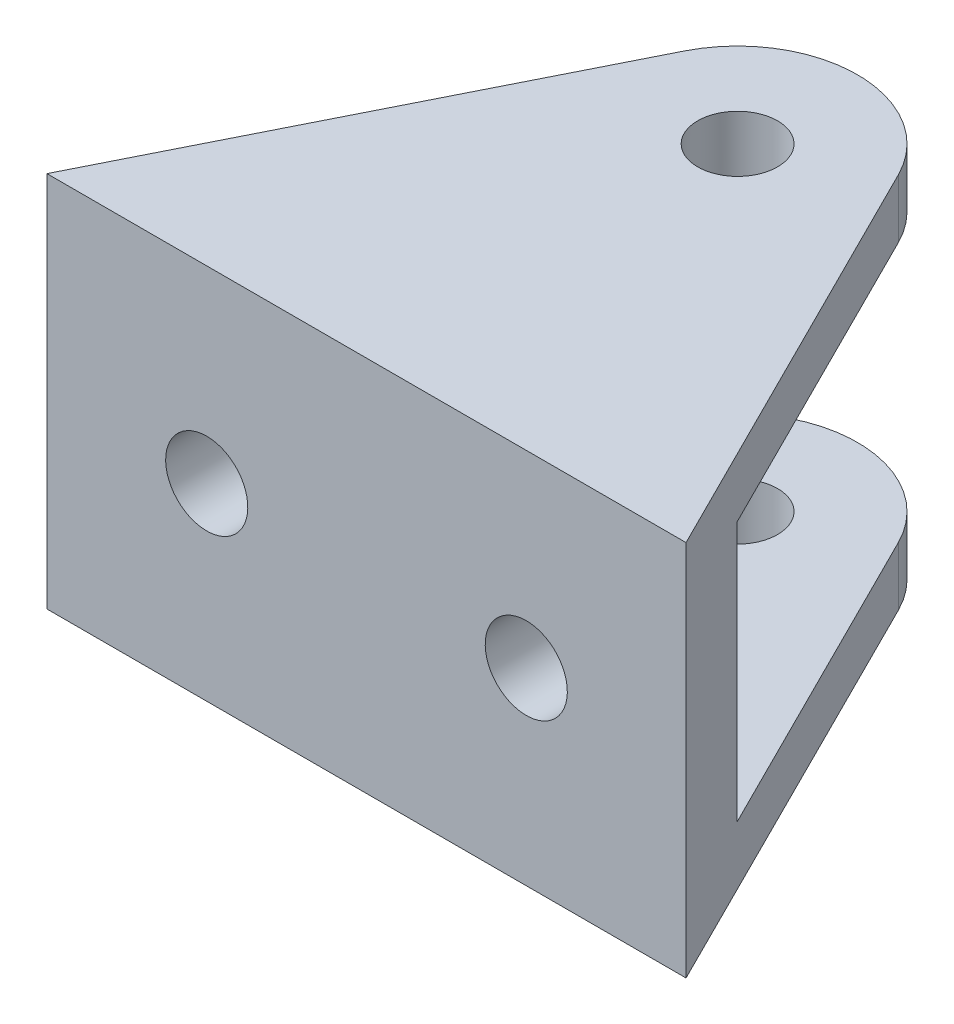
SolidWorks part; units mm, degrees
material "6061-T6 (SS)"
ref_plane "X-Y Datum" through (0, 0, 0) normal (0, 0, 1) x (1, 0, 0)
ref_plane "X-Z Datum" through (0, 0, 0) normal (0, 1, 0) x (1, 0, 0)
ref_plane "Y-Z Datum" through (0, 0, 0) normal (1, 0, 0) x (0, 0, -1)
sketch "Sketch1" plane through (0, 0, 0) normal (1, 0, 0) x (0, 0, -1)
  line L0 (0, 0) -> (0, 29.972)
  line L1 (0, 29.972) -> (39.8563, 29.972)
  line L2 (39.8563, 29.972) -> (39.8563, 25.3111)
  line L3 (39.8563, 25.3111) -> (8.1063, 25.3111)
  line L4 (8.1063, 25.3111) -> (8.1063, 4.6609)
  line L5 (8.1063, 4.6609) -> (39.8563, 4.6609)
  line L6 (39.8563, 4.6609) -> (39.8563, 0)
  line L7 (39.8563, 0) -> (0, 0)
  line L8 (27.1563, 29.972) -> (27.1563, 0) construction
  dimension "D1" = 20.6502
  dimension "D2" = 12.7
  dimension "D3" = 31.75
  dimension "D4" = 29.972
extrude "Boss-Extrude1" add sketch "Sketch1" along normal blind 50.8
sketch "Sketch2" plane through (0, 0, -8.1063) normal (0, 0, -1) x (-1, 0, 0)
  line L0 (-25.4, 25.3111) -> (-25.4, 4.6609) construction
  line L1 (-50.8, 25.3111) -> (0, 25.3111) construction
  line L2 (-50.8, 4.6609) -> (0, 4.6609) construction
  line L3 (-38.1, 14.986) -> (-12.7, 14.986) construction
  point P8 (-25.4, 14.986)
  point P9 (-25.4, 14.986)
  point P11 (-38.1, 14.986)
  point P12 (-12.7, 14.986)
  dimension "D1" = 25.4
hole_wizard "CBORE for 1/4 Binding Head Machine Screw1" positions "Sketch2" profile "Sketch3" counterbore size "1/4" standard "ANSI Inch" end condition through all
sketch "Sketch3" plane through (12.7, 14.986, -8.1063) normal (1, 0, 0) x (0, 1, 0)
  line L0 (0, 0) -> (0, 8.1063)
  line L1 (0, 8.1063) -> (3.2639, 8.1063)
  line L3 (3.2639, 8.1063) -> (3.2639, 3.302)
  line L4 (3.2639, 3.302) -> (7.1437, 3.302)
  line L5 (7.1437, 3.302) -> (7.1437, 0)
  line L7 (7.1437, 0) -> (0, 0)
  line L11 (0, -6.35) -> (0, 107.95) construction
  dimension "Thru Hole Dia." = 6.5278
  dimension "Thru Hole Depth" = 8.1063
  dimension "C'Bore Dia." = 14.2875
  dimension "C'Bore Depth" = 3.302
sketch "Sketch4" plane through (0, 0, 0) normal (0, -1, 0) x (1, 0, 0)
  line L0 (25.4, -39.8563) -> (25.4, 0) construction
  line L1 (50.8, -39.8563) -> (0, -39.8563) construction
  line L2 (50.8, 0) -> (0, 0) construction
  line L3 (0, 0) -> (16.8808, -33.7579)
  line L4 (50.8, 0) -> (33.9192, -33.7579)
  line L5 (0, 0) -> (0, -39.8563)
  line L6 (0, -39.8563) -> (50.8, -39.8563)
  line L7 (50.8, -39.8563) -> (50.8, 0)
  circle A0 centre (25.4, -29.4978) radius 3.175
  arc A1 (16.8808, -33.7579) -> (33.9192, -33.7579) centre (25.4, -29.4978) ccw
  dimension "D1" = 6.35
  dimension "D2" = 6.35
extrude "Cut-Extrude1" cut sketch "Sketch4" against normal up to surface (29.972 mm away) up to face at (25.4, 29.972, -19.9282)
